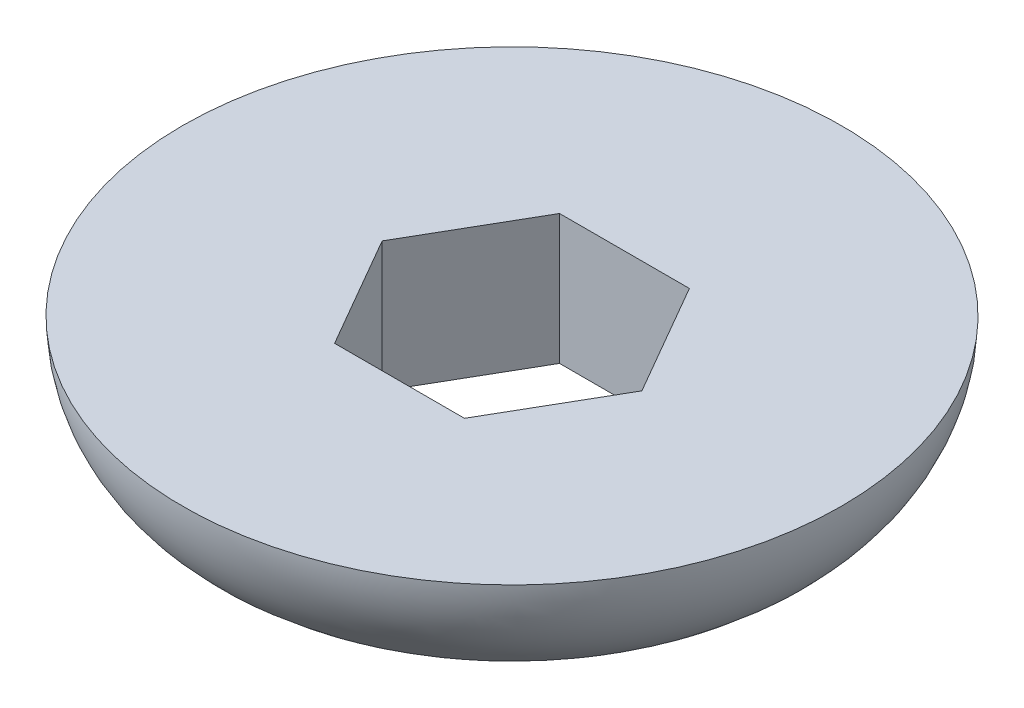
SolidWorks part; units mm, degrees
ref_plane "Front Plane" through (0, 0, 0) normal (0, 0, 1) x (1, 0, 0)
ref_plane "Top Plane" through (0, 0, 0) normal (0, 1, 0) x (1, 0, 0)
ref_plane "Right Plane" through (0, 0, 0) normal (1, 0, 0) x (0, 0, -1)
sketch "Sketch1" plane through (0, 0, 0) normal (0, 0, 1) x (1, 0, 0)
  line L0 (0, 0) -> (6, 0)
  line L2 (10.1512, 4) -> (0, 4)
  line L3 (0, 4) -> (0, 0)
  arc A0 (10.1512, 4) -> (6, 0) centre (6.0756, 4.0756) cw
  dimension "D1" = 6
  dimension "D2" = 4
revolve "Revolve1" add sketch "Sketch1" angle 360 about L3
sketch "Sketch2" plane through (0, 0, 0) normal (0, -1, 0) x (1, 0, 0)
  line L1 (4, 0) -> (2, 3.4641)
  line L2 (2, 3.4641) -> (-2, 3.4641)
  line L3 (-2, 3.4641) -> (-4, 0)
  line L4 (-4, 0) -> (-2, -3.4641)
  line L5 (-2, -3.4641) -> (2, -3.4641)
  line L6 (2, -3.4641) -> (4, 0)
  circle A0 centre (0, 0) radius 4 construction
extrude "Cut-Extrude1" cut sketch "Sketch2" against normal blind 4.8
